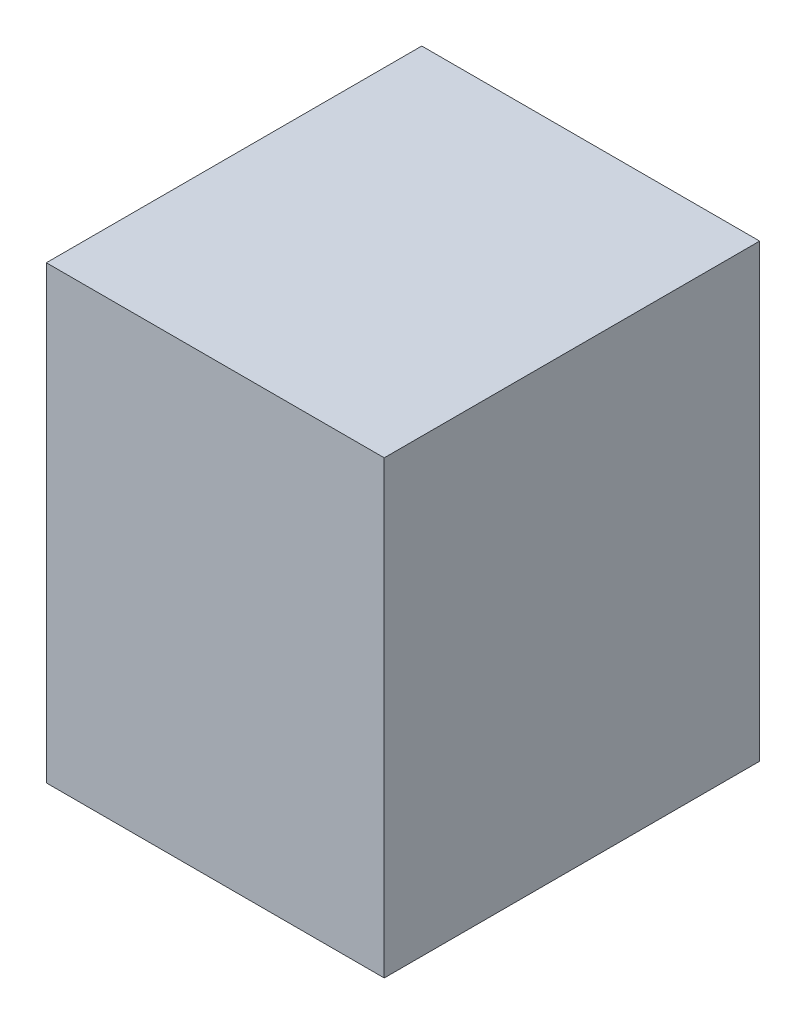
SolidWorks part; units mm, degrees
ref_plane "Front Plane" through (0, 0, 0) normal (0, 0, 1) x (1, 0, 0)
ref_plane "Top Plane" through (0, 0, 0) normal (0, 1, 0) x (1, 0, 0)
ref_plane "Right Plane" through (0, 0, 0) normal (1, 0, 0) x (0, 0, -1)
sketch "Sketch1" plane through (0, 0, 0) normal (0, 0, 1) x (1, 0, 0)
  line L1 (0, 0) -> (57.15, 0)
  line L2 (0, 0) -> (0, 76.2)
  line L3 (0, 76.2) -> (57.15, 76.2)
  line L4 (57.15, 0) -> (57.15, 76.2)
  dimension "D1" = 76.2
  dimension "D2" = 57.15
extrude "Boss-Extrude1" add sketch "Sketch1" along normal blind 63.5
sketch "Sketch2" plane through (0, 0, 0) normal (0, 0, -1) x (-1, 0, 0)
  line L0 (-57.15, 76.2) -> (0, 76.2) construction
  line L1 (0, 76.2) -> (-28.575, 76.2) construction
  line L2 (-28.575, 76.2) -> (-28.575, 0) construction
  line L3 (0, 0) -> (-57.15, 0) construction
  circle A1 centre (-28.575, 38.1) radius 22.225
  dimension "D1" = 44.45
extrude "Cut-Extrude1" cut sketch "Sketch2" against normal blind 29.21
